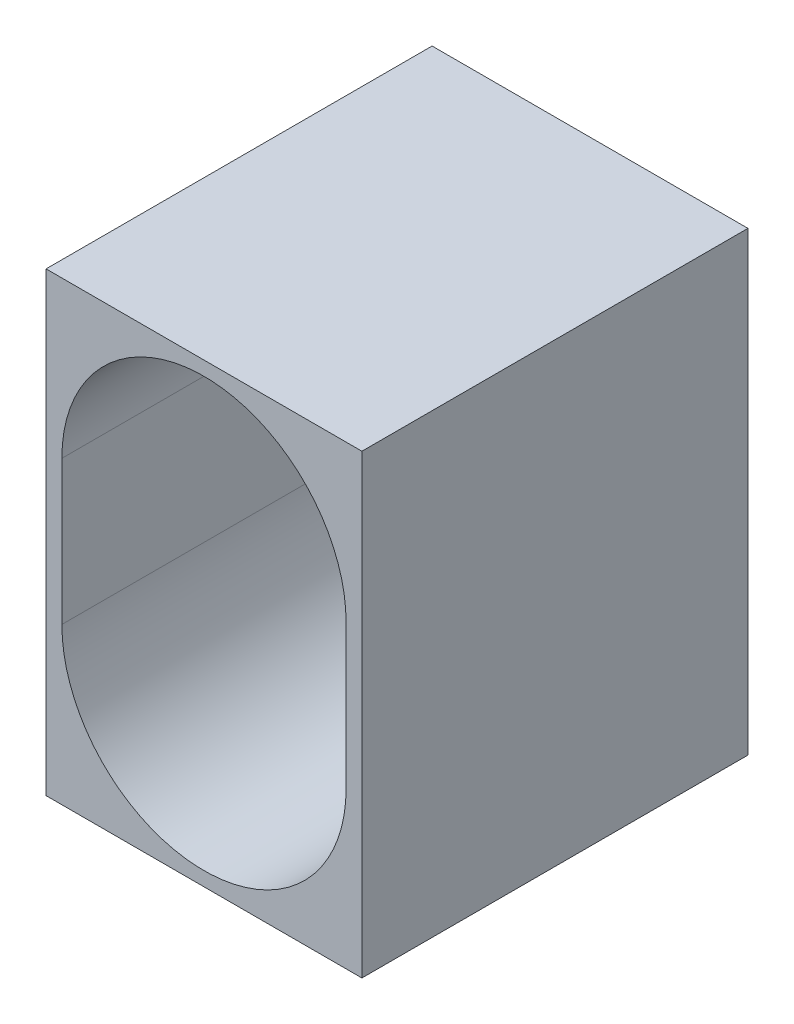
SolidWorks part; units mm, degrees
material "6061 Alloy"
ref_plane "Front Plane" through (0, 0, 0) normal (0, 0, 1) x (1, 0, 0)
ref_plane "Top Plane" through (0, 0, 0) normal (0, 1, 0) x (1, 0, 0)
ref_plane "Right Plane" through (0, 0, 0) normal (1, 0, 0) x (0, 0, -1)
sketch "Sketch4" plane through (0, 0, 0) normal (0, 0, 1) x (1, 0, 0)
  line L1 (-30.2849, 20.5607) -> (14.7151, 20.5607)
  line L2 (-30.2849, 20.5607) -> (-30.2849, -44.4393)
  line L3 (-30.2849, -44.4393) -> (14.7151, -44.4393)
  line L4 (14.7151, 20.5607) -> (14.7151, -44.4393)
  dimension "D1" = 45
  dimension "D2" = 65
extrude "Boss-Extrude2" add sketch "Sketch4" along normal blind 55
sketch "Sketch5" plane through (0, 0, 55) normal (0, 0, 1) x (1, 0, 0)
  line L0 (-7.7849, -22.1893) -> (-7.7849, -1.6893) construction
  line L1 (-21.0349, -22.1893) -> (-21.0349, -1.6893) construction
  line L2 (5.4651, -22.1893) -> (5.4651, -1.6893) construction
  line L3 (-30.2849, -44.4393) -> (14.7151, -44.4393) construction
  line L4 (-30.2849, 20.5607) -> (-30.2849, -44.4393) construction
  line L5 (-28.0349, -22.1893) -> (-28.0349, -1.6893)
  line L6 (12.4651, -22.1893) -> (12.4651, -1.6893)
  arc A0 (-21.0349, -22.1893) -> (5.4651, -22.1893) centre (-7.7849, -22.1893) ccw construction
  arc A1 (5.4651, -1.6893) -> (-21.0349, -1.6893) centre (-7.7849, -1.6893) ccw construction
  arc A2 (12.4651, -1.6893) -> (-28.0349, -1.6893) centre (-7.7849, -1.6893) ccw
  arc A3 (-28.0349, -22.1893) -> (12.4651, -22.1893) centre (-7.7849, -22.1893) ccw
  point P2 (-7.7849, -11.9393)
  dimension "D3" = 7
  dimension "D1" = 32.5
  dimension "D2" = 22.5
extrude "Cut-Extrude1" cut sketch "Sketch5" against normal blind 52.5
hole_wizard "1/4-28 Tapped Hole1" positions "Sketch6" profile "Sketch7" tap size "1/4-28" standard "ANSI Inch" end condition up to next
sketch "Sketch6" plane through (0, 0, 0) normal (0, 0, -1) x (-1, 0, 0)
  line L0 (-14.7151, -44.4393) -> (-14.7151, 20.5607) construction
  line L1 (-14.7151, 20.5607) -> (30.2849, 20.5607) construction
  point P0 (7.7849, -16.4393)
  dimension "D1" = 22.5
  dimension "D2" = 37
sketch "Sketch7" plane through (-7.7849, -16.4393, 0) normal (1, 0, 0) x (0, 1, 0)
  line L0 (0, 0) -> (0, 2.5)
  line L1 (0, 2.5) -> (2.7051, 2.5)
  line L2 (2.7051, 2.5) -> (2.7051, 0)
  line L5 (2.7051, 0) -> (0, 0)
  line L11 (0, -6.35) -> (0, 107.95) construction
  dimension "Thru Tap Drill Dia." = 5.4102
  dimension "Thru Tap Drill Depth" = 2.5
cosmetic thread "Hole Thread1" parameters "D2"=6.35
hole_wizard "Tap Drill for M2x0.4 Tap2" positions "Sketch14" profile "Sketch15" hole size "M2x0.4" standard "ANSI Metric"
sketch "Sketch14" plane through (0, 0, 0) normal (0, 0, -1) x (-1, 0, 0)
  line L0 (-14.7151, -44.4393) -> (-14.7151, 20.5607) construction
  line L1 (30.2849, -44.4393) -> (-14.7151, -44.4393) construction
  point P0 (-10.7151, -40.4393)
  dimension "D1" = 4
  dimension "D2" = 4
sketch "Sketch15" plane through (10.7151, -40.4393, 0) normal (1, 0, 0) x (0, 1, 0)
  line L0 (0, 0) -> (0, 8.4807)
  line L1 (0, 8.4807) -> (0.8, 8)
  line L2 (0.8, 8) -> (0.8, 0)
  line L5 (0.8, 0) -> (0, 0)
  line L10 (0, 8.4807) -> (-0.8, 8) construction
  line L11 (0, -6.35) -> (0, 107.95) construction
  dimension "Hole Dia." = 1.6
  dimension "Hole Depth" = 8
  dimension "Drill Angle" = 118
hole_wizard "Tap Drill for M2x0.4 Tap3" positions "3DSketch2" profile "Sketch19" hole size "M2x0.4" standard "ANSI Metric"
sketch3d "3DSketch2"
  line L0 (-30.2849, 20.5607, 0) -> (-30.2849, -44.4393, 0) construction
  line L1 (-30.2849, -44.4393, 0) -> (14.7151, -44.4393, 0) construction
  point P0 (-26.2849, -40.4393, 0)
  dimension "D1" = 4
  dimension "D2" = 4
sketch "Sketch19" plane through (-26.2849, -40.4393, 0) normal (1, 0, 0) x (0, 1, 0)
  line L0 (0, 0) -> (0, 8.4807)
  line L1 (0, 8.4807) -> (0.8, 8)
  line L2 (0.8, 8) -> (0.8, 0)
  line L5 (0.8, 0) -> (0, 0)
  line L10 (0, 8.4807) -> (-0.8, 8) construction
  line L11 (0, -6.35) -> (0, 107.95) construction
  dimension "Hole Dia." = 1.6
  dimension "Hole Depth" = 8
  dimension "Drill Angle" = 118
